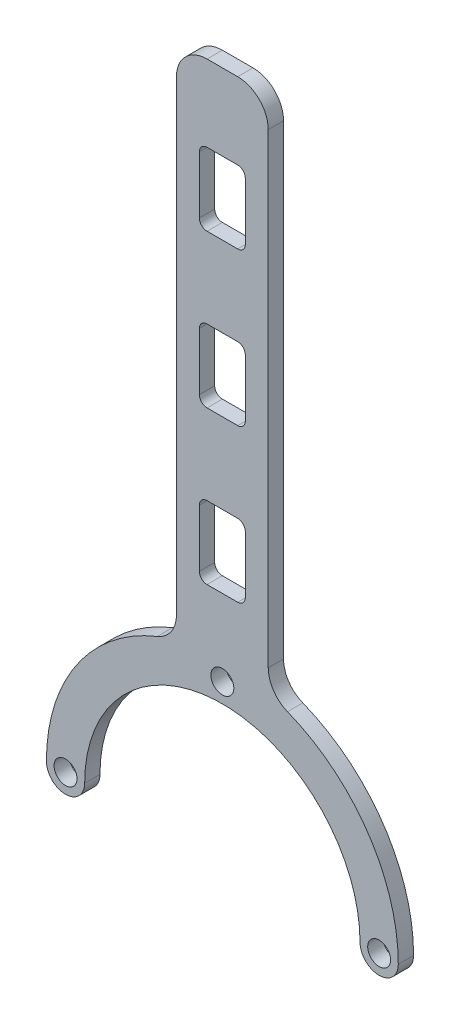
SolidWorks part; units mm, degrees
material "碳板"
ref_plane "前视基准面" through (0, 0, 0) normal (0, 0, 1) x (1, 0, 0)
ref_plane "上视基准面" through (0, 0, 0) normal (0, 1, 0) x (1, 0, 0)
ref_plane "右视基准面" through (0, 0, 0) normal (1, 0, 0) x (0, 0, -1)
sketch "草图1" plane through (0, 0, 0) normal (0, 0, 1) x (1, 0, 0)
  line L0 (0, 105.215) -> (0, -46.8475) construction
  line L1 (6, 90) -> (-6, 90)
  line L2 (-6, 90) -> (-6, 22.2036)
  line L3 (6, 90) -> (6, 22.2036)
  line L4 (-43.1325, 0) -> (47.1889, 0) construction
  line L5 (-3, 80) -> (3, 80)
  line L6 (-3, 80) -> (-3, 70.5)
  line L7 (-3, 70.5) -> (3, 70.5)
  line L8 (3, 80) -> (3, 70.5)
  line L9 (-3, 80) -> (3, 70.5) construction
  line L10 (-3, 70.5) -> (3, 80) construction
  line L11 (-3, 60) -> (-3, 50.5)
  line L12 (-3, 60) -> (3, 60)
  line L13 (3, 60) -> (3, 50.5)
  line L14 (-3, 50.5) -> (3, 50.5)
  line L15 (-3, 40) -> (-3, 30.5)
  line L16 (-3, 40) -> (3, 40)
  line L17 (3, 40) -> (3, 30.5)
  line L18 (-3, 30.5) -> (3, 30.5)
  line L19 (-3, 80) -> (-3, 60) construction
  circle A0 centre (0, 0) radius 23
  circle A2 centre (0, 0) radius 20.5 construction
  circle A3 centre (0, 20.5) radius 1.5
  circle A4 centre (-20.5, 0) radius 1.5
  circle A5 centre (20.5, 0) radius 1.5
  circle A6 centre (0, 0) radius 18
  circle A7 centre (-20.5, 0) radius 2.5
  circle A8 centre (20.5, 0) radius 2.5
  point P20 (0, 90)
  point P21 (0, 75.25)
  dimension "D1" = 46
  dimension "D2" = 41
  dimension "D3" = 5
  dimension "D4" = 3
  dimension "D5" = 12
  dimension "D6" = 3
  dimension "D7" = 90
  dimension "D8" = 10
  dimension "D10" = 20
  dimension "D11" = 10
  dimension "D9" = 3
extrude "凸台-拉伸1" add sketch "草图1" along normal blind 2 contours A8 A0 A7 A6 A3 | A0 L3 L1 L2 L5 L8 L7 L6 L14 L11 L12 L13 L18 L15 L16 L17 | A4 | A5
fillet "圆角1" radius 1 12 edges at (3, 30.5, 1) (3, 40, 1) (-3, 40, 1) (-3, 30.5, 1) (3, 50.5, 1) (3, 60, 1) (-3, 60, 1) (-3, 50.5, 1) (-3, 70.5, 1) (3, 70.5, 1) (3, 80, 1) (-3, 80, 1)
fillet "圆角2" radius 4 4 edges at (6, 90, 1) (-6, 90, 1) (6, 22.2036, 1) (-6, 22.2036, 1)
